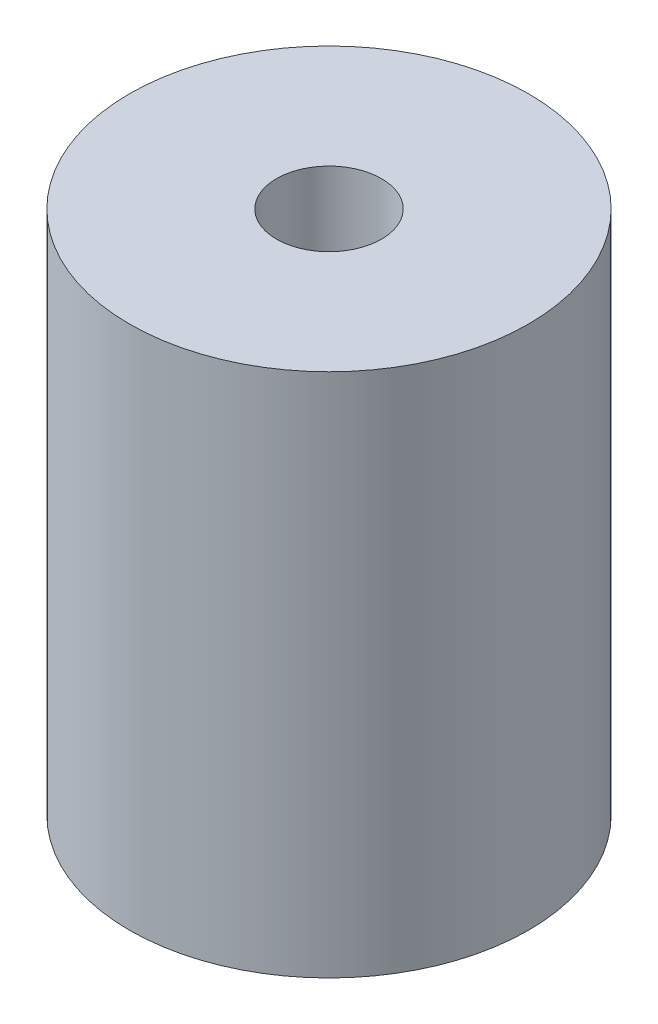
SolidWorks part; units mm, degrees
material "Liga 1060"
ref_plane "Plano frontal" through (0, 0, 0) normal (0, 0, 1) x (1, 0, 0)
ref_plane "Plano superior" through (0, 0, 0) normal (0, 1, 0) x (1, 0, 0)
ref_plane "Plano direito" through (0, 0, 0) normal (1, 0, 0) x (0, 0, -1)
sketch "Esboço1" plane through (0, 0, 0) normal (0, 1, 0) x (1, 0, 0)
  circle A0 centre (0, 0) radius 9.5
  dimension "D1" = 19
extrude "Ressalto-extrusão1" add sketch "Esboço1" along normal blind 25
sketch "Esboço2" plane through (0, 25, 0) normal (0, 1, 0) x (1, 0, 0)
  circle A0 centre (0, 0) radius 2.5
  dimension "D1" = 5
extrude "Corte-extrusão1" cut sketch "Esboço2" against normal blind 13
sketch "Esboço3" plane through (0, 0, 0) normal (0, -1, 0) x (1, 0, 0)
  circle A0 centre (0, 0) radius 4
  dimension "D1" = 8
extrude "Corte-extrusão2" cut sketch "Esboço3" against normal blind 13
